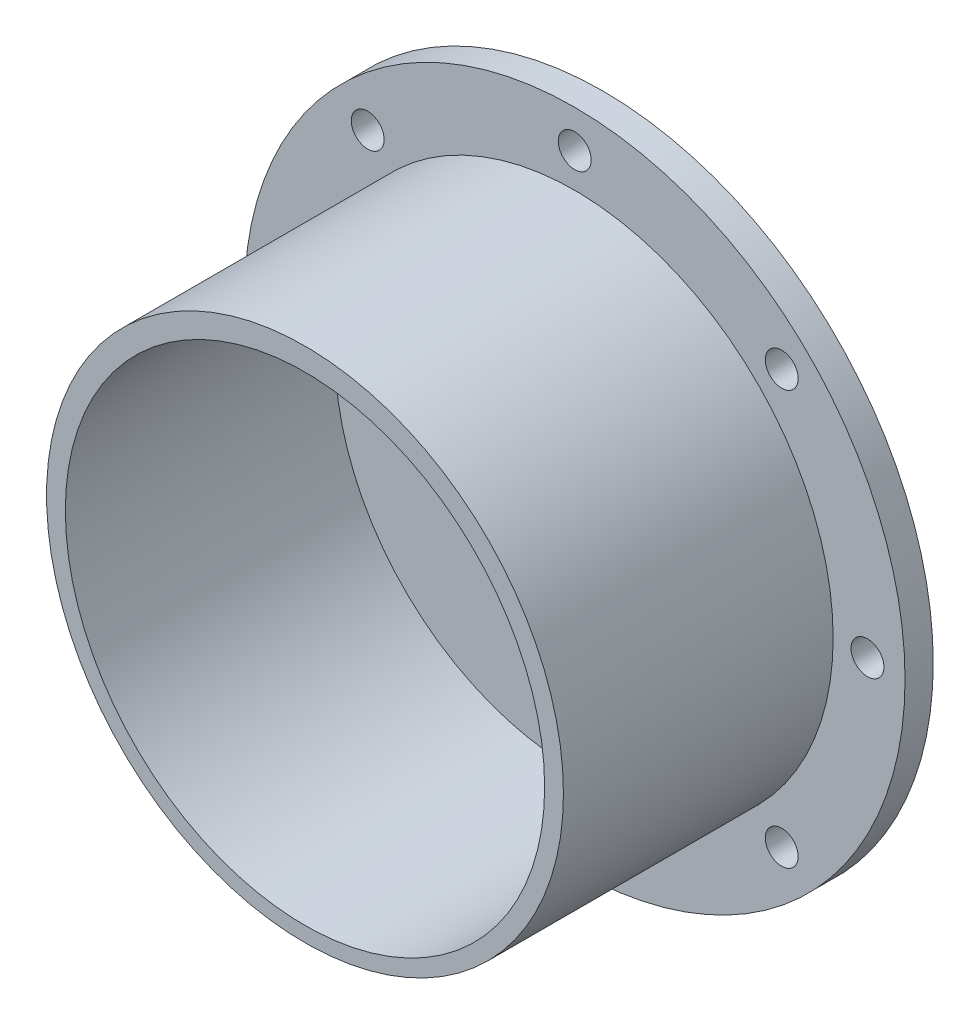
SolidWorks part; units mm, degrees
ref_plane "Ön Düzlem" through (0, 0, 0) normal (0, 0, 1) x (1, 0, 0)
ref_plane "Üst Düzlem" through (0, 0, 0) normal (0, 1, 0) x (1, 0, 0)
ref_plane "Sağ Düzlem" through (0, 0, 0) normal (1, 0, 0) x (0, 0, -1)
sketch "Çizim2" plane through (0, 0, 0) normal (0, 0, 1) x (1, 0, 0)
  circle A0 centre (0, 0) radius 35.15
  circle A1 centre (0, 31.1507) radius 1.75
  circle A2 centre (22.0269, 22.0269) radius 1.75
  circle A3 centre (31.1507, 0) radius 1.75
  circle A4 centre (22.0269, -22.0269) radius 1.75
  circle A5 centre (0, -31.1507) radius 1.75
  circle A6 centre (-22.0269, -22.0269) radius 1.75
  circle A7 centre (-31.1507, 0) radius 1.75
  circle A8 centre (-22.0269, 22.0269) radius 1.75
  dimension "D1" = 70.3
  dimension "D2" = 3.5
  dimension "D3" = 8
extrude "Yükseklik-Ekstrüzyon1" add sketch "Çizim2" along normal blind 3
sketch "Çizim3" plane through (0, 0, 3) normal (0, 0, 1) x (1, 0, 0)
  circle A0 centre (0, 0) radius 27.5
  circle A1 centre (0, -0.4005) radius 25.5
  dimension "D1" = 55
  dimension "D2" = 51
extrude "Yükseklik-Ekstrüzyon2" add sketch "Çizim3" along normal blind 28.7
